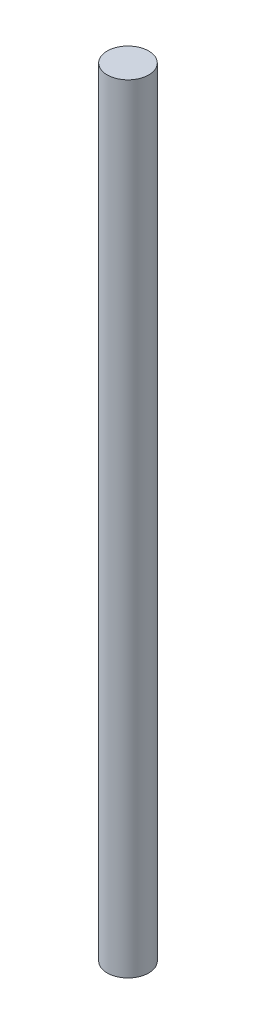
SolidWorks part; units mm, degrees
ref_plane "Plan de face" through (0, 0, 0) normal (1, 0, 0) x (0, 1, 0)
ref_plane "Plan de dessus" through (0, 0, 0) normal (0, 0, 1) x (0, 1, 0)
ref_plane "Plan de droite" through (0, 0, 0) normal (0, 1, 0) x (-1, 0, 0)
sketch "Esquisse1" plane through (0, 0, 0) normal (0, 1, 0) x (-1, 0, 0)
  circle A0 centre (0, 0) radius 4
  dimension "D1" = 8
extrude "Boss.-Extru.1" add sketch "Esquisse1" along normal blind 150
